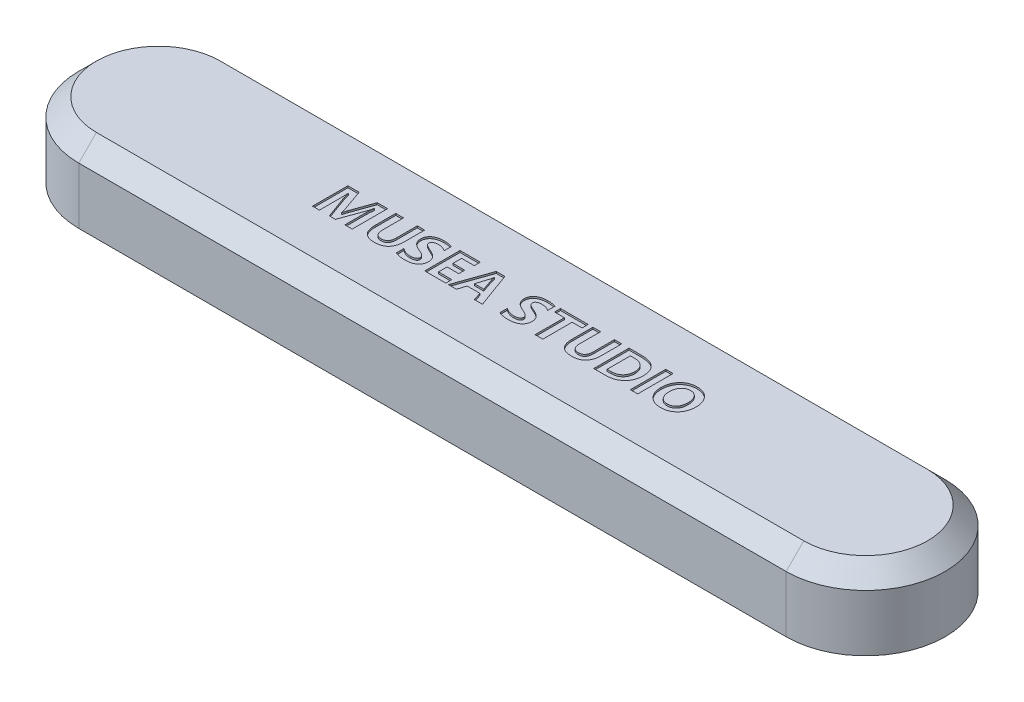
SolidWorks part; units mm, degrees
ref_plane "前视基准面" through (0, 0, 0) normal (0, 0, 1) x (1, 0, 0)
ref_plane "上视基准面" through (0, 0, 0) normal (0, 1, 0) x (1, 0, 0)
ref_plane "右视基准面" through (0, 0, 0) normal (1, 0, 0) x (0, 0, -1)
other "Configuration Table"
sketch "草图1" plane through (0, 0, 0) normal (0, 1, 0) x (1, 0, 0)
  line L1 (-100, 22.5) -> (100, 22.5)
  line L2 (-100, 22.5) -> (-100, -22.5)
  line L3 (-100, -22.5) -> (100, -22.5)
  line L4 (100, 22.5) -> (100, -22.5)
  line L5 (-100, 22.5) -> (100, -22.5) construction
  line L6 (-100, -22.5) -> (100, 22.5) construction
  circle A0 centre (-100, 0) radius 22.5
  circle A1 centre (100, 0) radius 22.5
  point P0 (0, 0)
  dimension "D1" = 200
  dimension "D2" = 45
extrude "凸台-拉伸1" add sketch "草图1" along normal blind 21 contours L2 A0 | L2 A0 | A1 L1 A0 L3 | L4 A1 | L4 A1
chamfer "倒角1" distance 5 angle 45 4 edges at (0, 21, -22.5) (-122.5, 21, 0) (122.5, 21, 0) (0, 21, 22.5)
shell "抽壳1" thickness 2.5
sketch "草图2" plane through (0, 0, 0) normal (0, -1, 0) x (1, 0, 0)
  line L0 (-100, -20) -> (100, -20) construction
  line L1 (-100, 20) -> (100, 20) construction
  line L2 (-100, -20) -> (100, -20)
  line L3 (-100, 20) -> (100, 20)
  line L4 (-100, -21.2) -> (100, -21.2)
  line L5 (-100, 21.2) -> (100, 21.2)
  arc A0 (100, -20) -> (100, 20) centre (100, 0) ccw construction
  arc A1 (-100, 20) -> (-100, -20) centre (-100, 0) ccw construction
  arc A2 (100, -20) -> (100, 20) centre (100, 0) ccw
  arc A3 (-100, 20) -> (-100, -20) centre (-100, 0) ccw
  arc A4 (-100, 21.2) -> (-100, -21.2) centre (-100, 0) ccw
  arc A5 (100, -21.2) -> (100, 21.2) centre (100, 0) ccw
  dimension "D1" = 1.2
extrude "切除-拉伸2" cut sketch "草图2" against normal blind 1.2
sketch "草图4" plane through (0, 18.5, 0) normal (0, -1, 0) x (1, 0, 0)
  line L0 (0, 0) -> (-15, 0) construction
  line L2 (-18.1177, 0) -> (-16.5588, -2.7) construction
  line L3 (-16.5588, -2.7) -> (-13.4412, -2.7) construction
  line L4 (-13.4412, -2.7) -> (-11.8823, 0) construction
  line L5 (-11.8823, 0) -> (-13.4412, 2.7) construction
  line L6 (-13.4412, 2.7) -> (-16.5588, 2.7) construction
  line L7 (-16.5588, 2.7) -> (-18.1177, 0) construction
  circle A0 centre (-15, 0) radius 5
  circle A1 centre (-15, 0) radius 2.7 construction
  dimension "D2" = 5.4
  dimension "D3" = 10
  dimension "D1" = 15
extrude "凸台-拉伸3" add sketch "草图4" along normal offset from surface (17.5 mm away) 1 up to face at (0, 0, 0)
sketch "草图5" plane through (0, 1, 0) normal (0, -1, 0) x (1, 0, 0)
  circle A0 centre (-15, 0) radius 1.6
  dimension "D1" = 3.2
extrude "切除-拉伸3" cut sketch "草图5" against normal blind 10
sketch "草图6" plane through (0, 1, 0) normal (0, -1, 0) x (1, 0, 0)
  line L1 (-13.4123, -2.75) -> (-11.8246, 0)
  line L2 (-11.8246, 0) -> (-13.4123, 2.75)
  line L3 (-13.4123, 2.75) -> (-16.5877, 2.75)
  line L4 (-16.5877, 2.75) -> (-18.1754, 0)
  line L5 (-18.1754, 0) -> (-16.5877, -2.75)
  line L6 (-16.5877, -2.75) -> (-13.4123, -2.75)
  circle A0 centre (-15, 0) radius 2.75 construction
  dimension "D1" = 5.5
extrude "切除-拉伸4" cut sketch "草图6" against normal blind 2.4
mirror "镜向1" about plane through (0, 0, 0) normal (1, 0, 0) of "切除-拉伸4", "凸台-拉伸3", "切除-拉伸3"
sketch "草图7" plane through (0, 21, 0) normal (0, 1, 0) x (1, 0, 0)
  line L0 (0, 0) -> (0, -5) construction
  line L1 (80, -5) -> (-80, -5) construction
  text T0 "<b>MUSEA STUDIO</b>" font "微软雅黑" height 10
  point P6 (0, 0)
  point P7 (0, -5)
  dimension "D1" = 160
  dimension "D2" = 5
extrude "切除-拉伸5" cut sketch "草图7" against normal blind 0.5
